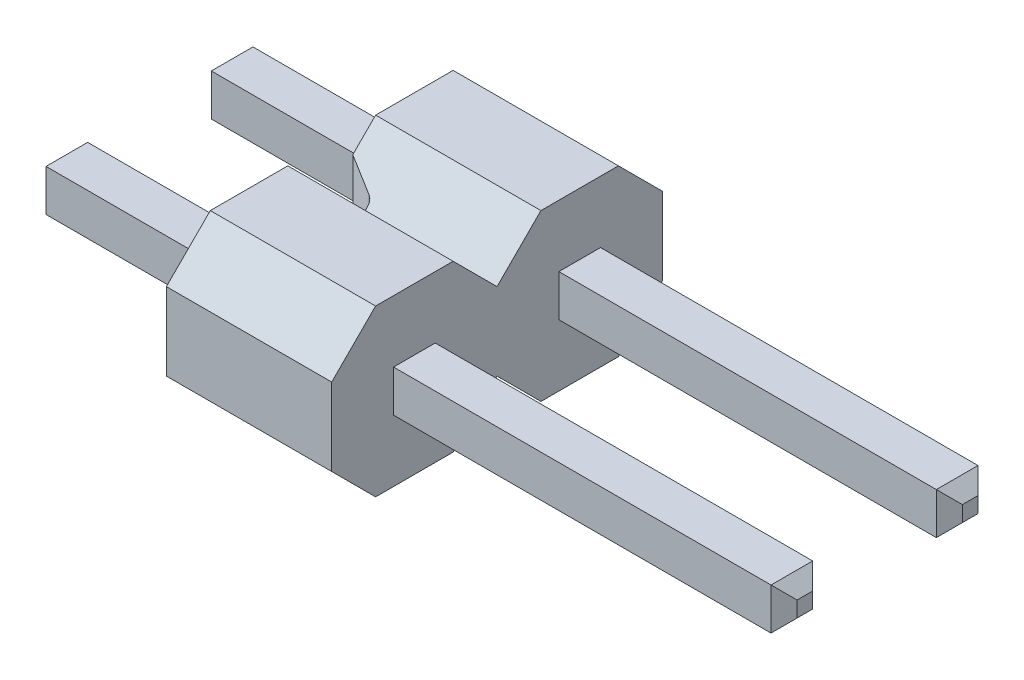
SolidWorks part; units mm, degrees
ref_plane "Alzado" through (0, 0, 0) normal (0, 0, 1) x (1, 0, 0)
ref_plane "Planta" through (0, 0, 0) normal (0, 1, 0) x (1, 0, 0)
ref_plane "Vista lateral" through (0, 0, 0) normal (1, 0, 0) x (0, 0, -1)
sketch "Croquis1" plane through (0, 0, 0) normal (1, 0, 0) x (0, 0, -1)
  line L0 (-0.5955, 1.27) -> (-1.27, 0.5955)
  line L1 (0.5955, 1.27) -> (-0.5955, 1.27)
  line L2 (1.27, 0.5955) -> (1.27, -0.5955)
  line L3 (0.5955, -1.27) -> (-0.5955, -1.27)
  line L4 (-1.27, 0.5955) -> (-1.27, -0.5955)
  line L5 (1.27, 1.27) -> (-1.27, -1.27) construction
  line L6 (1.27, -1.27) -> (-1.27, 1.27) construction
  line L7 (-0.5955, -1.27) -> (-1.27, -0.5955)
  line L8 (1.27, -0.5955) -> (0.5955, -1.27)
  line L9 (1.27, 0.5955) -> (0.5955, 1.27)
  line L10 (0, 0) -> (2.54, 0) construction
  line L11 (2.54, 0) -> (2.54, 3.1915) construction
  line L12 (0, 0) -> (0, 2.4434) construction
  line L13 (1.27, 0.5955) -> (1.27, 2.4434) construction
  line L14 (1.27, -0.5955) -> (1.9445, -1.27)
  line L15 (1.27, 0.5955) -> (1.9445, 1.27)
  line L16 (3.1355, -1.27) -> (3.81, -0.5955)
  line L17 (3.81, 0.5955) -> (3.81, -0.5955)
  line L18 (1.9445, -1.27) -> (3.1355, -1.27)
  line L19 (1.9445, 1.27) -> (3.1355, 1.27)
  line L20 (3.1355, 1.27) -> (3.81, 0.5955)
  line L21 (2.22, -0.32) -> (2.86, 0.32) construction
  line L22 (0.32, 0.32) -> (-0.32, 0.32)
  line L23 (0.32, 0.32) -> (0.32, -0.32)
  line L24 (0.32, -0.32) -> (-0.32, -0.32)
  line L25 (-0.32, 0.32) -> (-0.32, -0.32)
  line L26 (0.32, 0.32) -> (-0.32, -0.32) construction
  line L27 (0.32, -0.32) -> (-0.32, 0.32) construction
  line L28 (2.22, 0.32) -> (2.86, -0.32) construction
  line L29 (2.86, 0.32) -> (2.86, -0.32)
  line L30 (2.22, -0.32) -> (2.86, -0.32)
  line L31 (2.22, 0.32) -> (2.22, -0.32)
  line L32 (2.22, 0.32) -> (2.86, 0.32)
  point P0 (0, 0)
  dimension "D1" = 2.54
  dimension "D2" = 2.54
  dimension "D3" = 2.54
  dimension "D4" = 0.64
  dimension "D5" = 0.64
extrude "Saliente-Extruir1" add sketch "Croquis1" along normal blind 2.54 contours L2 L9 L1 L0 L4 L7 L3 L8 L25 L22 L23 L24 | L20 L19 L15 L2 L14 L18 L16 L17 L31 L32 L29 L30
sketch "Croquis2" plane through (0, 0, 0) normal (0, 1, 0) x (1, 0, 0)
  line L0 (0, 1.27) -> (0.5165, 1.27) construction
  line L1 (2.54, 1.27) -> (0, 1.27) construction
  line L2 (0.5165, 1.2433) -> (0.5165, 1.2967)
  line L3 (0.4575, 1.3879) -> (0, 1.5936)
  line L4 (0, 1.27) -> (0, 1.9445) construction
  line L5 (0.4575, 1.1521) -> (0, 0.9464)
  line L6 (0, 1.5936) -> (0, 0.9464)
  arc A0 (0.5165, 1.2967) -> (0.4575, 1.3879) centre (0.4165, 1.2967) ccw
  arc A1 (0.5165, 1.2433) -> (0.4575, 1.1521) centre (0.4165, 1.2433) cw
  dimension "D1" = 0.1
extrude "Cortar-Extruir1" cut sketch "Croquis2" against normal blind 2.54 and the other way blind 2.54
sketch "Croquis3" plane through (0, 0, 0) normal (1, 0, 0) x (0, 0, -1)
  line L1 (-0.32, -0.32) -> (0.32, -0.32)
  line L2 (-0.32, -0.32) -> (-0.32, 0.32)
  line L3 (-0.32, 0.32) -> (0.32, 0.32)
  line L4 (0.32, -0.32) -> (0.32, 0.32)
  line L5 (2.22, -0.32) -> (2.86, -0.32)
  line L6 (2.22, -0.32) -> (2.22, 0.32)
  line L7 (2.22, 0.32) -> (2.86, 0.32)
  line L8 (2.86, -0.32) -> (2.86, 0.32)
extrude "Saliente-Extruir2" add sketch "Croquis3" along normal blind 8.54 and the other way blind 3 separate body
chamfer "Chaflán1" distance 0.2 angle 45 8 edges at (-3, -0.32, 0) (-3, 0, -0.32) (-3, 0.32, 0) (-3, 0, 0.32) (8.54, 0.32, 0) (8.54, 0, -0.32) (8.54, -0.32, 0) (8.54, 0, 0.32)
chamfer "Chaflán2" distance 0.2 angle 45 8 edges at (8.54, 0.32, -2.54) (8.54, 0, -2.86) (8.54, -0.32, -2.54) (8.54, 0, -2.22) (-3, -0.32, -2.54) (-3, 0, -2.86) (-3, 0.32, -2.54) (-3, 0, -2.22)
